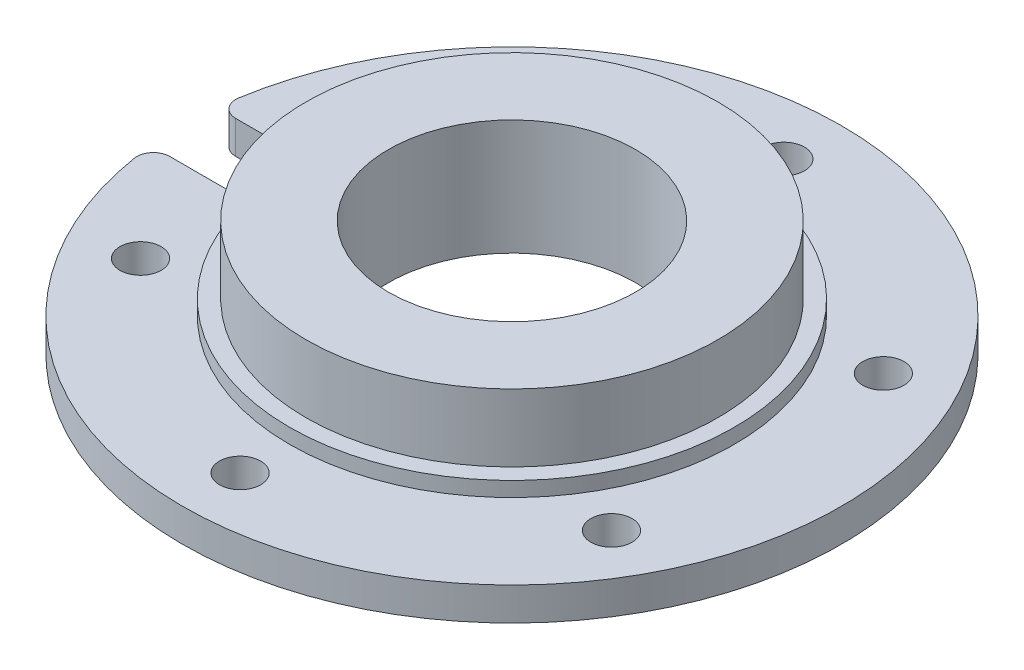
SolidWorks part; units mm, degrees
material "6061 合金"
ref_plane "前视基准面" through (0, 0, 0) normal (0, 0, 1) x (1, 0, 0)
ref_plane "上视基准面" through (0, 0, 0) normal (0, 1, 0) x (1, 0, 0)
ref_plane "右视基准面" through (0, 0, 0) normal (1, 0, 0) x (0, 0, -1)
other "Configuration Table"
sketch "草图1" plane through (0, 0, 0) normal (0, 1, 0) x (1, 0, 0)
  circle A0 centre (0, 0) radius 20
  circle A1 centre (0, 0) radius 7.5
  circle A2 centre (0, 0) radius 16.5 construction
  circle A3 centre (0, 16.5) radius 1
  circle A4 centre (14.2894, 8.25) radius 1
  circle A5 centre (14.2894, -8.25) radius 1
  circle A6 centre (0, -16.5) radius 1
  circle A7 centre (-14.2894, -8.25) radius 1
  circle A8 centre (-14.2894, 8.25) radius 1
  point P20 (0, 0)
  dimension "D1" = 40
  dimension "D2" = 15
  dimension "D3" = 33
  dimension "D4" = 2
extrude "凸台-拉伸1" add sketch "草图1" along normal blind 2
sketch "草图2" plane through (0, 2, 0) normal (0, 1, 0) x (1, 0, 0)
  circle A1 centre (0, 0) radius 7.5
  circle A2 centre (0, 0) radius 12.5
  circle A3 centre (0, 0) radius 7.5 construction
  dimension "D1" = 25
extrude "凸台-拉伸2" add sketch "草图2" along normal blind 5
sketch "草图3" plane through (0, 2, 0) normal (0, 1, 0) x (1, 0, 0)
  circle A0 centre (0, 0) radius 12.5
  circle A1 centre (0, 0) radius 12.5 construction
  circle A2 centre (0, 0) radius 13.5
  dimension "D1" = 1
extrude "凸台-拉伸3" add sketch "草图3" along normal blind 0.9
sketch "草图4" plane through (0, 0, 0) normal (0, -1, 0) x (1, 0, 0)
  line L0 (0, 0) -> (-20, 0) construction
  line L2 (-23.1889, 2) -> (-14, 2)
  line L3 (-23.1889, 2) -> (-23.1889, -2)
  line L4 (-23.1889, -2) -> (-14, -2)
  line L5 (-14, 2) -> (-14, -2)
  circle A0 centre (0, 0) radius 20 construction
  dimension "D1" = 14
  dimension "D2" = 2
extrude "切除-拉伸1" cut sketch "草图4" against normal blind 10
fillet "圆角1" radius 1 4 edges at (-14, 1, 2) (-19.8997, 1, 2) (-19.8997, 1, -2) (-14, 1, -2)
hole_wizard "M3 螺纹孔1" positions "草图7" profile "草图6" tap size "M3" standard "GB" end condition through all
sketch "草图7" plane through (0, 0, 0) normal (0, -1, 0) x (1, 0, 0)
  point P0 (-14.2894, 8.25)
  point P3 (0, 16.5)
  point P6 (14.2894, 8.25)
  point P9 (14.2894, -8.25)
  point P12 (0, -16.5)
  point P15 (-14.2894, -8.25)
sketch "草图6" plane through (-14.2894, 0, 8.25) normal (1, 0, 0) x (0, 0, -1)
  line L0 (0, 0) -> (0, 7)
  line L1 (0, 7) -> (1.25, 7)
  line L2 (1.25, 7) -> (1.25, 0)
  line L5 (1.25, 0) -> (0, 0)
  line L11 (0, -6.35) -> (0, 107.95) construction
  dimension "通孔螺纹孔钻头直径" = 2.5
  dimension "通孔螺纹孔钻头深度" = 7
cosmetic thread "孔螺纹线1" parameters "D2"=3
cosmetic thread "孔螺纹线2" parameters "D2"=3
cosmetic thread "孔螺纹线3" parameters "D2"=3
cosmetic thread "孔螺纹线4" parameters "D2"=3
cosmetic thread "孔螺纹线5" parameters "D2"=3
cosmetic thread "孔螺纹线6" parameters "D2"=3
